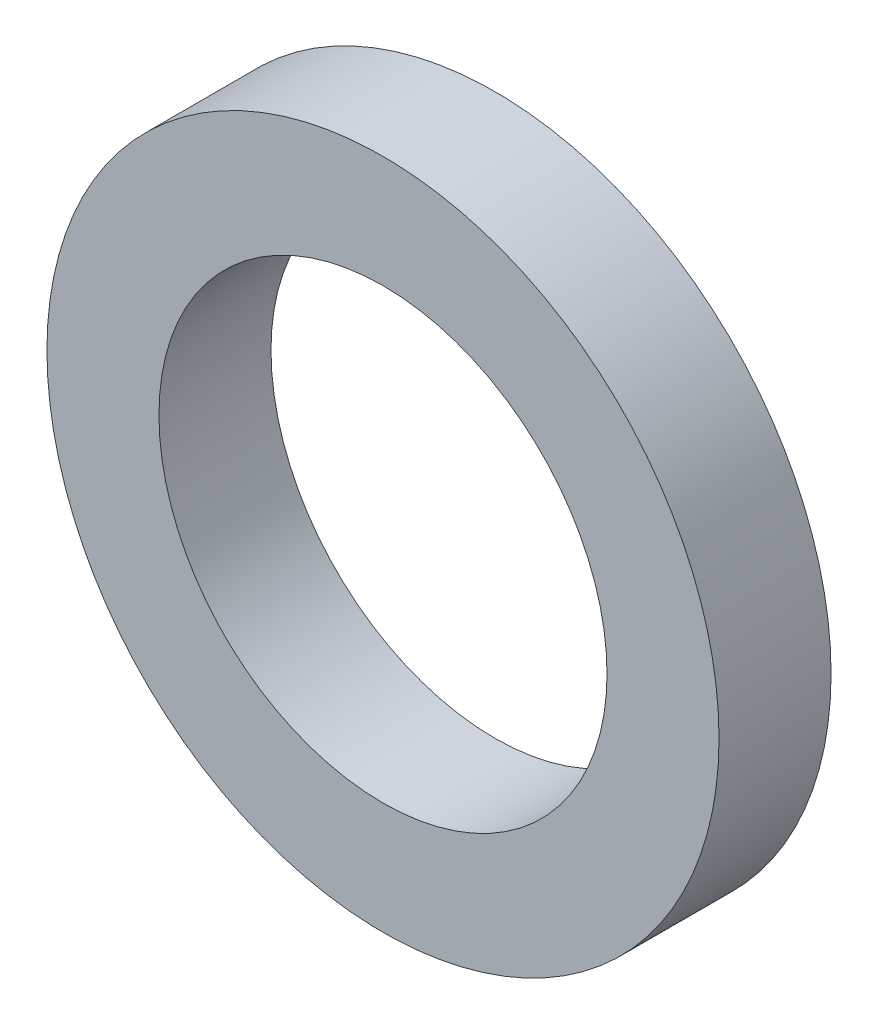
SolidWorks part; units mm, degrees
material "NBR"
ref_plane "Front Plane" through (0, 0, 0) normal (0, 0, 1) x (1, 0, 0)
ref_plane "Top Plane" through (0, 0, 0) normal (0, 1, 0) x (1, 0, 0)
ref_plane "Right Plane" through (0, 0, 0) normal (1, 0, 0) x (0, 0, -1)
sketch "Sketch1" plane through (0, 0, 0) normal (0, 1, 0) x (1, 0, 0)
  line L0 (14, 97) -> (21, 97)
  line L1 (21, 97) -> (21, 104)
  line L2 (21, 104) -> (14, 104)
  line L3 (14, 104) -> (14, 97)
  line L4 (0, -150) -> (0, 150) construction
revolve "REV_Radial_Seal_28x42x7_envelope" add sketch "Sketch1" angle 360 about L4
